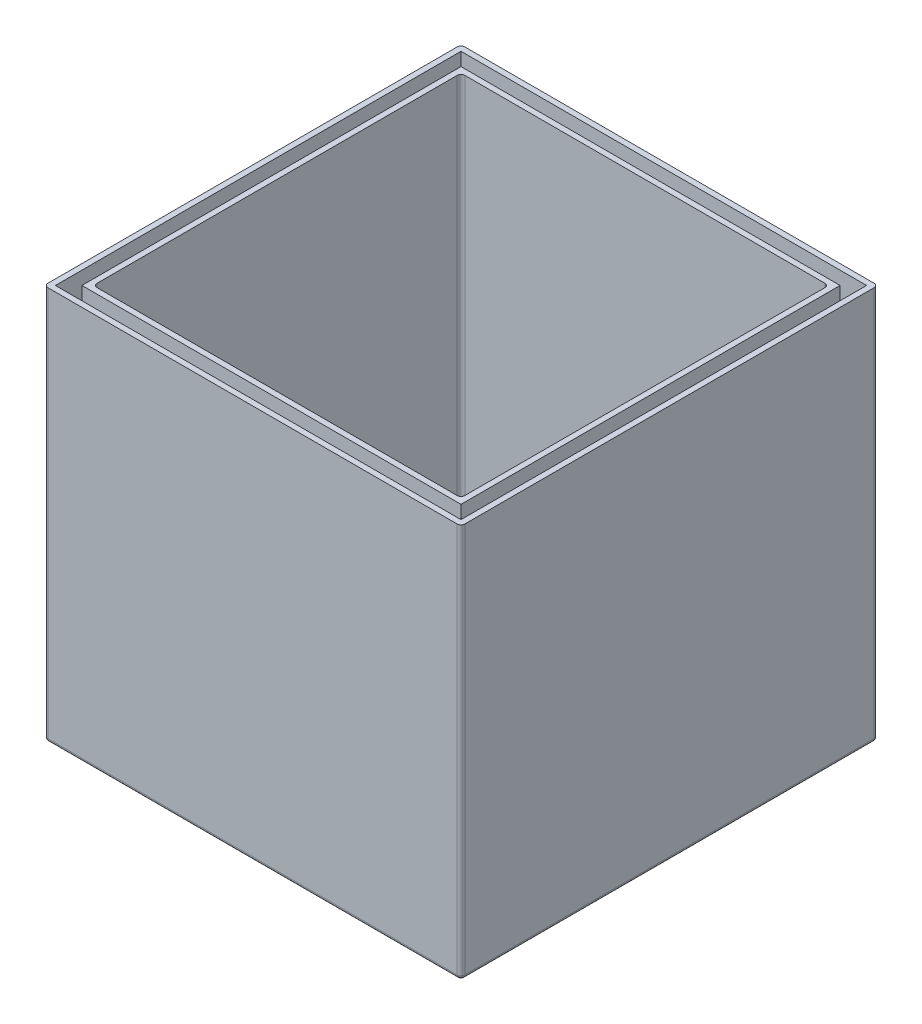
SolidWorks part; units mm, degrees
material "Nylon 101"
ref_plane "Front Plane" through (0, 0, 0) normal (0, 0, 1) x (1, 0, 0)
ref_plane "Top Plane" through (0, 0, 0) normal (0, 1, 0) x (1, 0, 0)
ref_plane "Right Plane" through (0, 0, 0) normal (1, 0, 0) x (0, 0, -1)
sketch "Sketch1" plane through (0, 0, 0) normal (0, 1, 0) x (1, 0, 0)
  line L0 (-100, 100) -> (100, 100)
  line L1 (-97, 97) -> (97, 97)
  line L2 (-97, 97) -> (-97, -97)
  line L3 (-97, -97) -> (97, -97)
  line L4 (97, 97) -> (97, -97)
  line L5 (-97, 97) -> (97, -97) construction
  line L6 (-97, -97) -> (97, 97) construction
  line L7 (100, 100) -> (100, -100)
  line L8 (-100, -100) -> (100, -100)
  line L9 (-100, 100) -> (-100, -100)
  line L10 (-107, -107) -> (107, -107)
  line L11 (107, 107) -> (107, -107)
  line L12 (-107, 107) -> (107, 107)
  line L13 (-107, 107) -> (-107, -107)
  line L14 (-110, -110) -> (110, -110)
  line L15 (110, 110) -> (110, -110)
  line L16 (-110, 110) -> (110, 110)
  line L17 (-110, 110) -> (-110, -110)
  point P0 (0, 0)
  dimension "D1" = 194
  dimension "D2" = 194
  dimension "D3" = 3
  dimension "D4" = 7
  dimension "D5" = 3
extrude "Boss-Extrude1" add sketch "Sketch1" along normal blind 205 contours L0 L9 L8 L7 L1 L4 L3 L2 | L16 L17 L14 L15 L13 L12 L11 L10
sketch "Sketch3" plane through (0, 0, 0) normal (0, -1, 0) x (1, 0, 0)
  line L1 (-110, -110) -> (110, -110)
  line L2 (-110, -110) -> (-110, 110)
  line L3 (-110, 110) -> (110, 110)
  line L4 (110, -110) -> (110, 110)
  line L5 (-110, -110) -> (110, 110) construction
  line L6 (-110, 110) -> (110, -110) construction
  point P0 (0, 0)
extrude "Boss-Extrude3" add sketch "Sketch3" along normal blind 3
fillet "Fillet1" radius 2 16 edges at (0, -3, -110) (-110, -3, 0) (0, -3, 110) (110, -3, 0) (97, 0, 0) (0, 0, 97) (-97, 0, 0) (0, 0, -97) (110, 101, -110) (110, 101, 110) (-110, 101, 110) (-110, 101, -110) (-97, 102.5, -97) (97, 102.5, -97) (-97, 102.5, 97) (97, 102.5, 97)
ref_plane "Plane1" through (0, 80, 0) normal (0, 1, 0) x (1, 0, 0)
